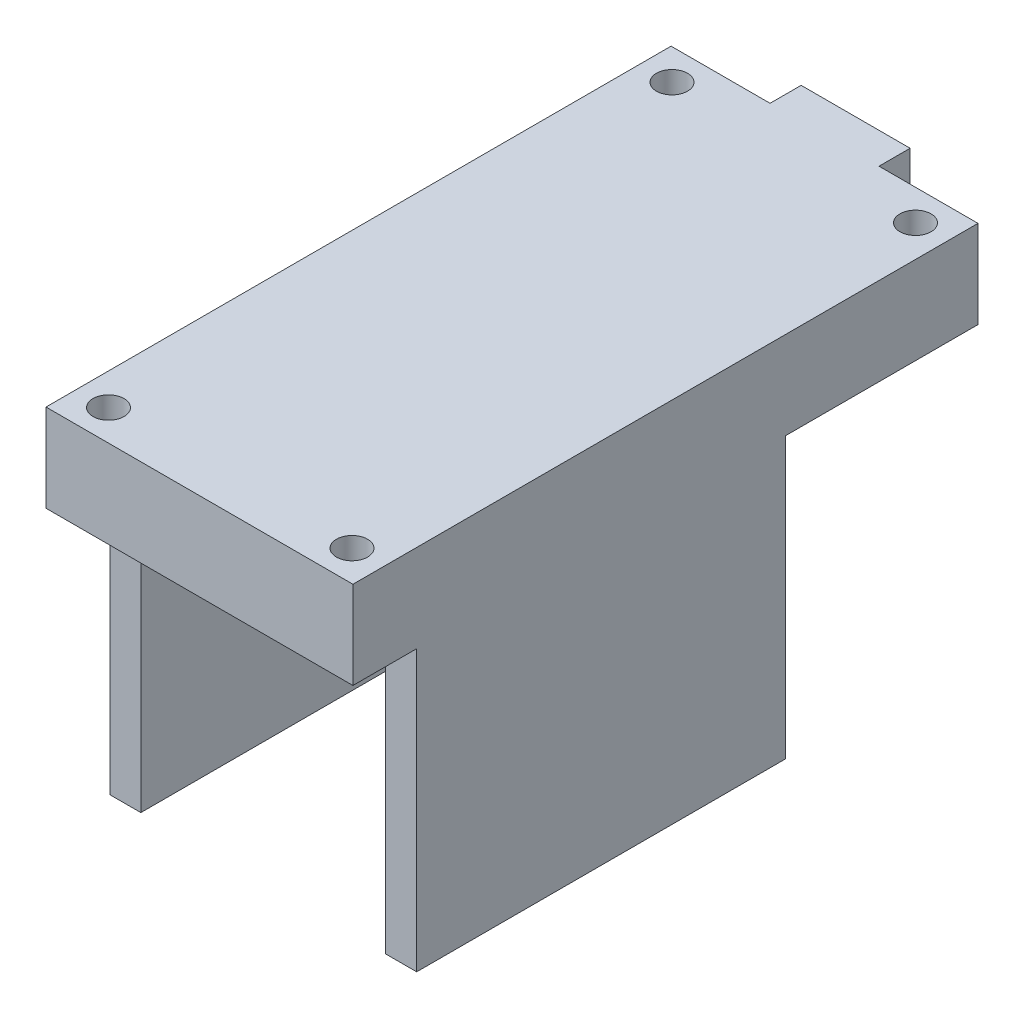
SolidWorks part; units mm, degrees
ref_plane "Front Plane" through (0, 0, 0) normal (0, 0, 1) x (1, 0, 0)
ref_plane "Top Plane" through (0, 0, 0) normal (0, 1, 0) x (1, 0, 0)
ref_plane "Right Plane" through (0, 0, 0) normal (1, 0, 0) x (0, 0, -1)
sketch "Sketch1" plane through (0, 0, 0) normal (0, 1, 0) x (1, 0, 0)
  line L0 (0, 0) -> (0, 13.8831) construction
  line L1 (-12.5349, -25.527) -> (12.5349, -25.527)
  line L2 (-12.5349, -25.527) -> (-12.5349, 25.527)
  line L3 (-12.5349, 25.527) -> (12.5349, 25.527)
  line L4 (12.5349, -25.527) -> (12.5349, 25.527)
  line L5 (-12.5349, -25.527) -> (12.5349, 25.527) construction
  line L6 (-12.5349, 25.527) -> (12.5349, -25.527) construction
  line L7 (0, 0) -> (-8.2851, 0) construction
  circle A0 centre (9.9441, 23.0124) radius 1.27
  circle A1 centre (-9.9441, 23.0124) radius 1.27
  circle A2 centre (9.9441, -23.0124) radius 1.27
  circle A3 centre (-9.9441, -23.0124) radius 1.27
  point P0 (0, 0)
  dimension "D3" = 2.54
  dimension "D5" = 2.5146
  dimension "D1" = 51.054
  dimension "D2" = 25.0698
  dimension "D4" = 2.5908
extrude "Boss-Extrude1" add sketch "Sketch1" along normal blind 7.1628
sketch "Sketch2" plane through (0, 0, 0) normal (0, -1, 0) x (1, 0, 0)
  line L0 (-12.5349, -25.527) -> (-12.5349, 25.527) construction
  line L1 (-12.5349, 20.32) -> (-9.9949, 20.32)
  line L2 (-12.5349, 20.32) -> (-12.5349, -20.32)
  line L3 (-12.5349, -20.32) -> (-9.9949, -20.32)
  line L4 (-9.9949, 20.32) -> (-9.9949, -20.32)
  line L5 (12.5349, 25.527) -> (12.5349, -25.527) construction
  line L6 (12.5349, 20.32) -> (9.9949, 20.32)
  line L7 (12.5349, 20.32) -> (12.5349, -9.8044)
  line L8 (12.5349, -9.8044) -> (9.9949, -9.8044)
  line L9 (9.9949, 20.32) -> (9.9949, -9.8044)
  line L10 (-12.5349, 25.527) -> (12.5349, 25.527) construction
  dimension "D1" = 5.207
  dimension "D2" = 30.1244
  dimension "D3" = 40.64
  dimension "D4" = 2.54
  dimension "D5" = 2.54
extrude "Boss-Extrude2" add sketch "Sketch2" along normal blind 22.86
sketch "Sketch3" plane through (0, 0, -25.527) normal (0, 0, -1) x (-1, 0, 0)
  line L0 (-12.5349, 7.1628) -> (12.5349, 7.1628) construction
  line L1 (-4.45, 7.1628) -> (4.45, 7.1628)
  line L2 (-4.45, 7.1628) -> (-4.45, 0)
  line L3 (-4.45, 0) -> (4.45, 0)
  line L4 (4.45, 7.1628) -> (4.45, 0)
  line L5 (-12.5349, 0) -> (12.5349, 0) construction
  line L6 (-12.5349, 7.1628) -> (12.5349, 7.1628)
  point P8 (0, 7.1628)
  line M5 (-12.5349, 0) -> (12.5349, 0)
  line M7 (12.5349, 7.1628) -> (-12.5349, 7.1628)
  dimension "D1" = 8.9
extrude "Boss-Extrude3" add sketch "Sketch3" along normal blind 2.54 contours L4 L2 M7 M5
